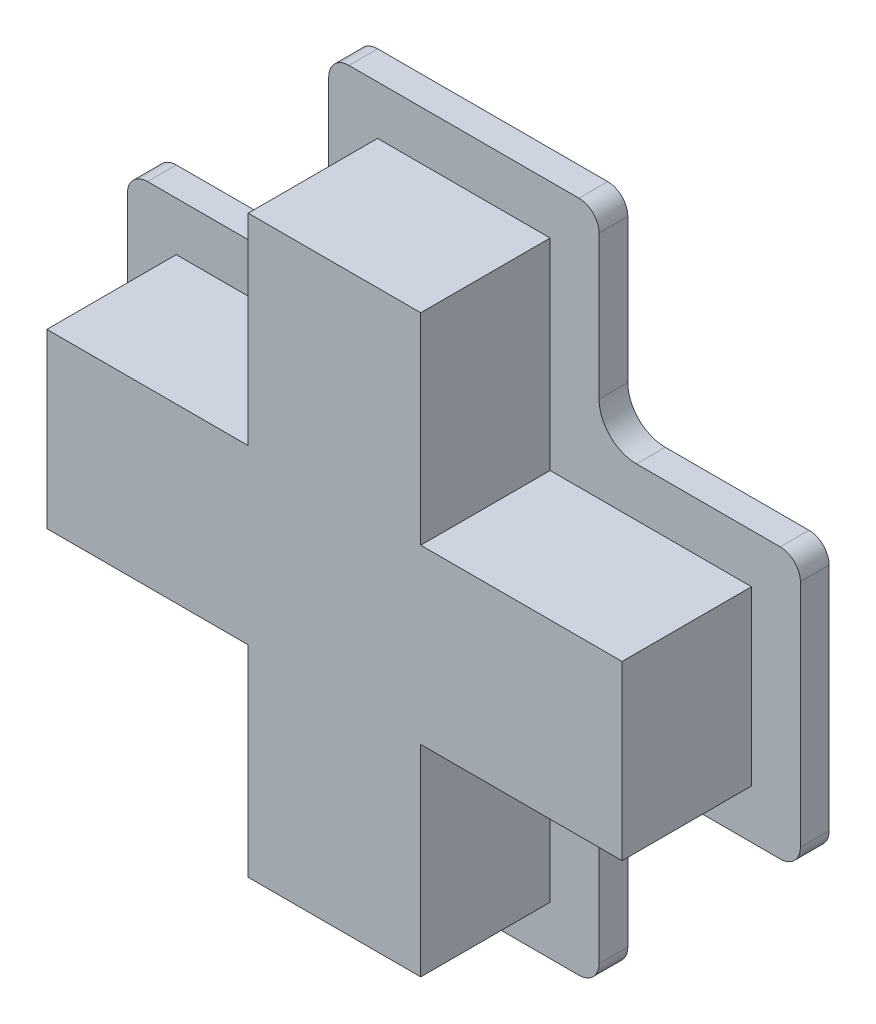
SolidWorks part; units mm, degrees
ref_plane "Front Plane" through (0, 0, 0) normal (0, 0, 1) x (1, 0, 0)
ref_plane "Top Plane" through (0, 0, 0) normal (0, 1, 0) x (1, 0, 0)
ref_plane "Right Plane" through (0, 0, 0) normal (1, 0, 0) x (0, 0, -1)
sketch "Sketch1" plane through (0, 0, 0) normal (0, 0, 1) x (1, 0, 0)
  line L92 (-14.1739, 7.0321) -> (-14.1739, 1.0321)
  line L93 (-14.1739, 1.0321) -> (-7.1739, 1.0321)
  line L94 (-7.1739, 1.0321) -> (-7.1739, -5.9679)
  line L95 (-7.1739, -5.9679) -> (-1.1739, -5.9679)
  line L96 (-1.1739, -5.9679) -> (-1.1739, 1.0321)
  line L97 (-1.1739, 1.0321) -> (5.8261, 1.0321)
  line L98 (5.8261, 1.0321) -> (5.8261, 7.0321)
  line L99 (5.8261, 7.0321) -> (-1.1739, 7.0321)
  line L100 (-1.1739, 7.0321) -> (-1.1739, 14.0321)
  line L101 (-1.1739, 14.0321) -> (-7.1739, 14.0321)
  line L102 (-7.1739, 14.0321) -> (-7.1739, 7.0321)
  line L103 (-7.1739, 7.0321) -> (-14.1739, 7.0321)
  line L104 (-14.1739, 7.0321) -> (-14.1739, 1.0321)
  line L105 (-14.1739, 1.0321) -> (-7.1739, 1.0321)
  line L106 (-7.1739, 1.0321) -> (-7.1739, -5.9679)
  line L107 (-7.1739, -5.9679) -> (-1.1739, -5.9679)
  line L108 (-1.1739, -5.9679) -> (-1.1739, 1.0321)
  line L109 (-1.1739, 1.0321) -> (5.8261, 1.0321)
  line L110 (5.8261, 1.0321) -> (5.8261, 7.0321)
  line L111 (5.8261, 7.0321) -> (-1.1739, 7.0321)
  line L112 (-1.1739, 7.0321) -> (-1.1739, 14.0321)
  line L113 (-1.1739, 14.0321) -> (-7.1739, 14.0321)
  line L114 (-7.1739, 14.0321) -> (-7.1739, 7.0321)
  line L115 (-7.1739, 7.0321) -> (-14.1739, 7.0321)
  dimension "D1" = 0.5
extrude "Boss-Extrude1" add sketch "Sketch1" along normal blind 5.5
sketch "Sketch2" plane through (0, 0, 0) normal (0, 0, 1) x (1, 0, 0)
  line L241 (-15.8739, 8.0321) -> (-15.8739, 0.0321)
  line L242 (-15.1739, -0.6679) -> (-10.1739, -0.6679)
  line L243 (-8.8739, -1.9679) -> (-8.8739, -6.9679)
  line L244 (-8.1739, -7.6679) -> (-0.1739, -7.6679)
  line L245 (0.5261, -6.9679) -> (0.5261, -1.9679)
  line L246 (1.8261, -0.6679) -> (6.8261, -0.6679)
  line L247 (7.5261, 0.0321) -> (7.5261, 8.0321)
  line L248 (6.8261, 8.7321) -> (1.8261, 8.7321)
  line L249 (0.5261, 10.0321) -> (0.5261, 15.0321)
  line L250 (-0.1739, 15.7321) -> (-8.1739, 15.7321)
  line L251 (-8.8739, 15.0321) -> (-8.8739, 10.0321)
  line L252 (-10.1739, 8.7321) -> (-15.1739, 8.7321)
  line L253 (-15.8739, 8.0321) -> (-15.8739, 0.0321)
  line L254 (-15.1739, -0.6679) -> (-10.1739, -0.6679)
  line L255 (-8.8739, -1.9679) -> (-8.8739, -6.9679)
  line L256 (-8.1739, -7.6679) -> (-0.1739, -7.6679)
  line L257 (0.5261, -6.9679) -> (0.5261, -1.9679)
  line L258 (1.8261, -0.6679) -> (6.8261, -0.6679)
  line L259 (7.5261, 0.0321) -> (7.5261, 8.0321)
  line L260 (6.8261, 8.7321) -> (1.8261, 8.7321)
  line L261 (0.5261, 10.0321) -> (0.5261, 15.0321)
  line L262 (-0.1739, 15.7321) -> (-8.1739, 15.7321)
  line L263 (-8.8739, 15.0321) -> (-8.8739, 10.0321)
  line L264 (-10.1739, 8.7321) -> (-15.1739, 8.7321)
  arc A168 (-15.8739, 0.0321) -> (-15.1739, -0.6679) centre (-15.1739, 0.0321) ccw
  arc A169 (-8.8739, -1.9679) -> (-10.1739, -0.6679) centre (-10.1739, -1.9679) ccw
  arc A170 (-8.8739, -6.9679) -> (-8.1739, -7.6679) centre (-8.1739, -6.9679) ccw
  arc A171 (-0.1739, -7.6679) -> (0.5261, -6.9679) centre (-0.1739, -6.9679) ccw
  arc A172 (1.8261, -0.6679) -> (0.5261, -1.9679) centre (1.8261, -1.9679) ccw
  arc A173 (6.8261, -0.6679) -> (7.5261, 0.0321) centre (6.8261, 0.0321) ccw
  arc A174 (7.5261, 8.0321) -> (6.8261, 8.7321) centre (6.8261, 8.0321) ccw
  arc A175 (0.5261, 10.0321) -> (1.8261, 8.7321) centre (1.8261, 10.0321) ccw
  arc A176 (0.5261, 15.0321) -> (-0.1739, 15.7321) centre (-0.1739, 15.0321) ccw
  arc A177 (-8.1739, 15.7321) -> (-8.8739, 15.0321) centre (-8.1739, 15.0321) ccw
  arc A178 (-10.1739, 8.7321) -> (-8.8739, 10.0321) centre (-10.1739, 10.0321) ccw
  arc A179 (-15.1739, 8.7321) -> (-15.8739, 8.0321) centre (-15.1739, 8.0321) ccw
  arc A180 (-15.8739, 0.0321) -> (-15.1739, -0.6679) centre (-15.1739, 0.0321) ccw
  arc A181 (-8.8739, -1.9679) -> (-10.1739, -0.6679) centre (-10.1739, -1.9679) ccw
  arc A182 (-8.8739, -6.9679) -> (-8.1739, -7.6679) centre (-8.1739, -6.9679) ccw
  arc A183 (-0.1739, -7.6679) -> (0.5261, -6.9679) centre (-0.1739, -6.9679) ccw
  arc A184 (1.8261, -0.6679) -> (0.5261, -1.9679) centre (1.8261, -1.9679) ccw
  arc A185 (6.8261, -0.6679) -> (7.5261, 0.0321) centre (6.8261, 0.0321) ccw
  arc A186 (7.5261, 8.0321) -> (6.8261, 8.7321) centre (6.8261, 8.0321) ccw
  arc A187 (0.5261, 10.0321) -> (1.8261, 8.7321) centre (1.8261, 10.0321) ccw
  arc A188 (0.5261, 15.0321) -> (-0.1739, 15.7321) centre (-0.1739, 15.0321) ccw
  arc A189 (-8.1739, 15.7321) -> (-8.8739, 15.0321) centre (-8.1739, 15.0321) ccw
  arc A190 (-10.1739, 8.7321) -> (-8.8739, 10.0321) centre (-10.1739, 10.0321) ccw
  arc A191 (-15.1739, 8.7321) -> (-15.8739, 8.0321) centre (-15.1739, 8.0321) ccw
  dimension "D1" = 0.3
extrude "Boss-Extrude2" add sketch "Sketch2" along normal blind 1
